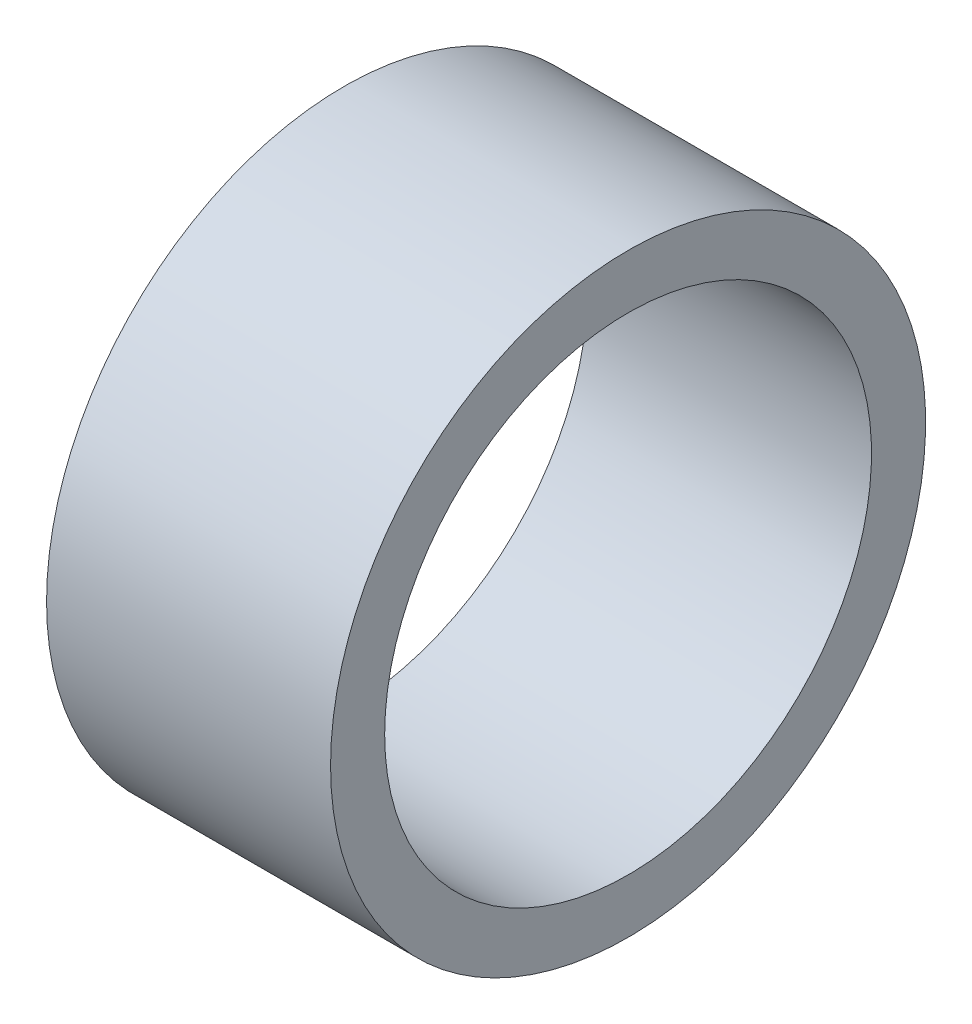
SolidWorks part; units mm, degrees
material "Laiton"
ref_plane "Plan de face" through (0, 0, 0) normal (0, 0, 1) x (1, 0, 0)
ref_plane "Plan de dessus" through (0, 0, 0) normal (0, 1, 0) x (1, 0, 0)
ref_plane "Plan de droite" through (0, 0, 0) normal (1, 0, 0) x (0, 0, -1)
ref_plane "Plan4" through (0, 0, 0) normal (0, 0, -1) x (-1, 0, 0)
sketch "Esquisse1" plane through (0, 0, 0) normal (0, 0, -1) x (-1, 0, 0)
  line L0 (-21, 22) -> (-21, 18)
  line L1 (-21, 18) -> (0, 18)
  line L2 (0, 18) -> (0, 22)
  line L3 (0, 22) -> (-21, 22)
  line L4 (-21, 0) -> (0, 0) construction
revolve "Révolution1" add sketch "Esquisse1" angle 360 about L4
